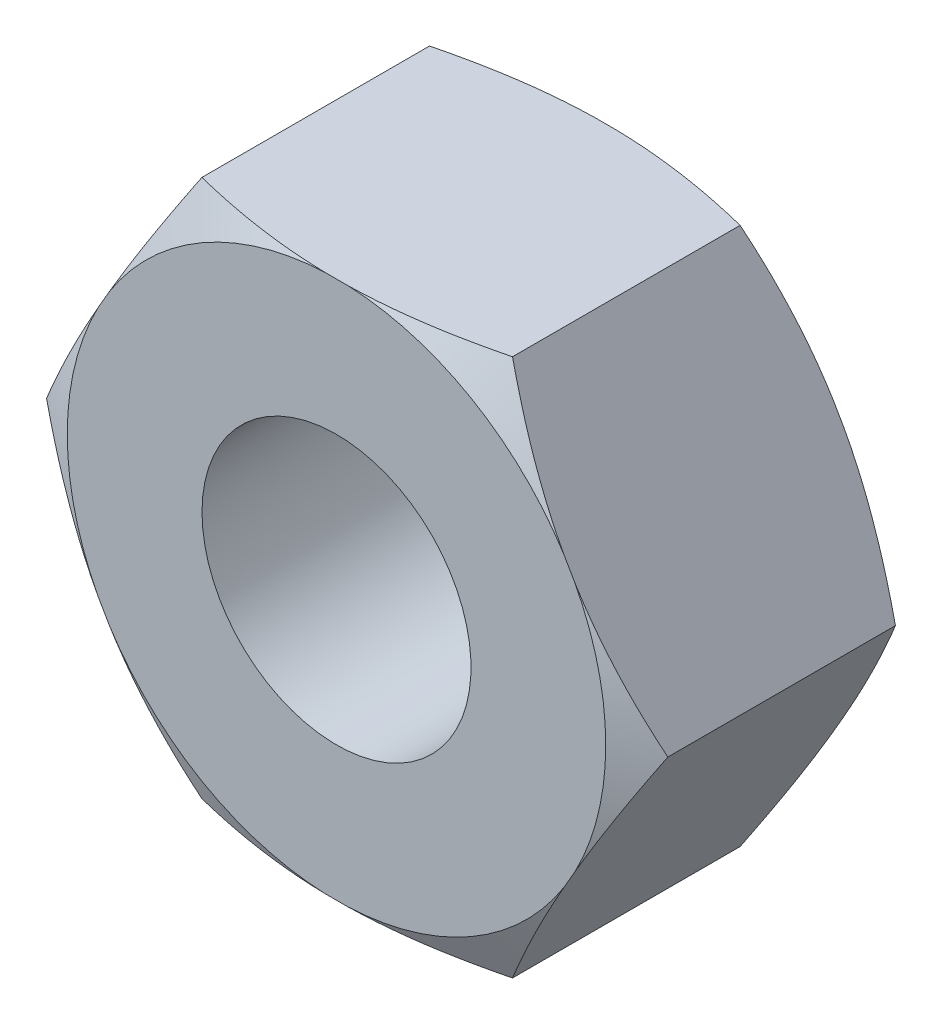
SolidWorks part; units mm, degrees
material "1.0037 (S235JR)"
ref_plane "Ön Düzlem" through (0, 0, 0) normal (0, 0, 1) x (1, 0, 0)
ref_plane "Üst Düzlem" through (0, 0, 0) normal (0, 1, 0) x (1, 0, 0)
ref_plane "Sağ Düzlem" through (0, 0, 0) normal (1, 0, 0) x (0, 0, -1)
sketch "Çizim1" plane through (0, 0, 0) normal (0, 0, 1) x (1, 0, 0)
  line L1 (7.5056, 0) -> (3.7528, 6.5)
  line L2 (3.7528, 6.5) -> (-3.7528, 6.5)
  line L3 (-3.7528, 6.5) -> (-7.5056, 0)
  line L4 (-7.5056, 0) -> (-3.7528, -6.5)
  line L5 (-3.7528, -6.5) -> (3.7528, -6.5)
  line L6 (3.7528, -6.5) -> (7.5056, 0)
  circle A0 centre (0, 0) radius 6.5 construction
  circle A1 centre (0, 0) radius 3.25
  dimension "D1" = 6.5
  dimension "D2" = 13
extrude "Yükseklik-Ekstrüzyon1" add sketch "Çizim1" along normal blind 6.5
cosmetic thread "Kozmetik Diş Açma1" parameters "D2"=8
sketch "Çizim2" plane through (0, 0, 0) normal (0, 1, 0) x (1, 0, 0)
  line L0 (-7.5056, 0) -> (-6.5056, 0)
  line L1 (-3.7528, 0) -> (-7.5056, 0) construction
  line L2 (-6.5056, 0) -> (-7.5056, -0.5)
  line L3 (-7.5056, -6.5) -> (-7.5056, 0) construction
  line L4 (-7.5056, -0.5) -> (-7.5056, 0)
  line L5 (-7.5056, -6.5) -> (-7.5056, -6)
  line L6 (-7.5056, -6) -> (-6.5056, -6.5)
  line L7 (-3.7528, -6.5) -> (-7.5056, -6.5) construction
  line L8 (-6.5056, -6.5) -> (-7.5056, -6.5)
  line L9 (0, 0) -> (0, -6.5) construction
  line L10 (3.7528, -6.5) -> (-3.7528, -6.5) construction
  dimension "D1" = 0.5
  dimension "D2" = 1
  dimension "D3" = 0.5
  dimension "D4" = 1
revolve "Kes-Döndür1" cut sketch "Çizim2" angle 360 about L9
